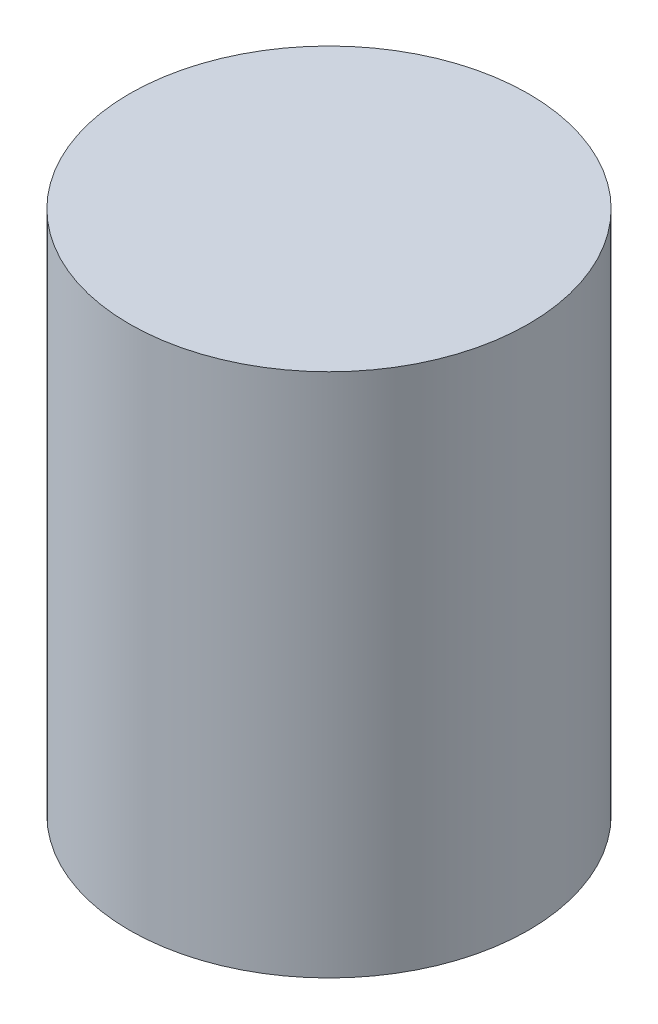
SolidWorks part; units mm, degrees
ref_plane "Plano frontal" through (0, 0, 0) normal (0, 0, 1) x (1, 0, 0)
ref_plane "Plano superior" through (0, 0, 0) normal (0, 1, 0) x (1, 0, 0)
ref_plane "Plano direito" through (0, 0, 0) normal (1, 0, 0) x (0, 0, -1)
sketch "Esboço1" plane through (0, 0, 0) normal (0, 1, 0) x (1, 0, 0)
  circle A0 centre (0, 0) radius 9.5
  dimension "D1" = 19
extrude "Ressalto-extrusão1" add sketch "Esboço1" along normal blind 25
